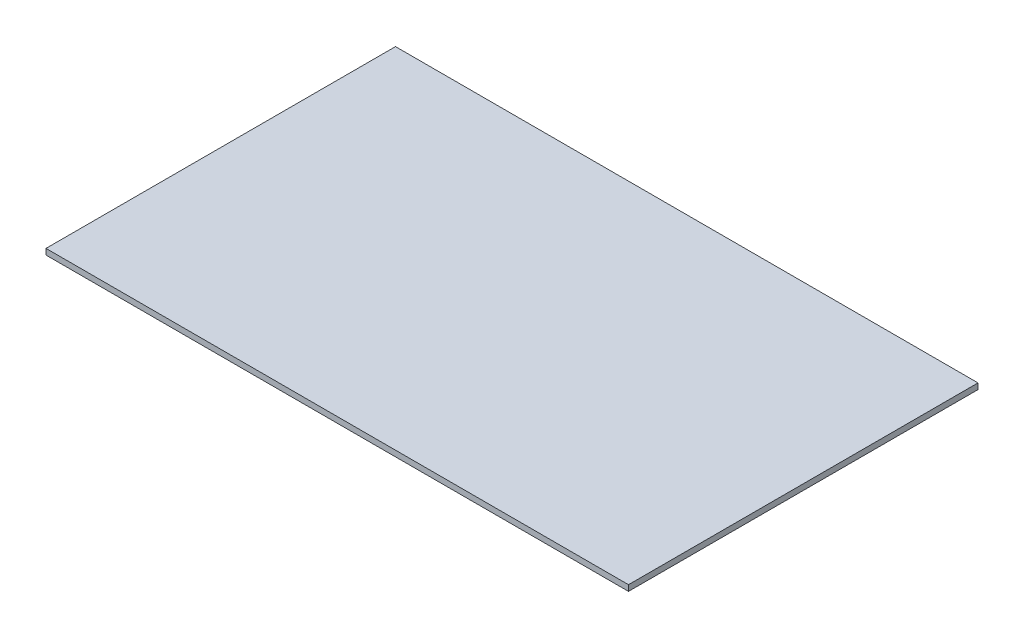
SolidWorks part; units mm, degrees
ref_plane "Front Plane" through (0, 0, 0) normal (0, 0, 1) x (1, 0, 0)
ref_plane "Top Plane" through (0, 0, 0) normal (0, 1, 0) x (1, 0, 0)
ref_plane "Right Plane" through (0, 0, 0) normal (1, 0, 0) x (0, 0, -1)
sketch "Sketch1" plane through (0, 0, 0) normal (0, 1, 0) x (1, 0, 0)
  line L1 (-250, 150) -> (250, 150)
  line L2 (-250, 150) -> (-250, -150)
  line L3 (-250, -150) -> (250, -150)
  line L4 (250, 150) -> (250, -150)
  line L5 (-250, 150) -> (250, -150) construction
  line L6 (-250, -150) -> (250, 150) construction
  point P0 (0, 0)
  dimension "D1" = 500
  dimension "D2" = 300
extrude "Boss-Extrude1" add sketch "Sketch1" along normal blind 5
